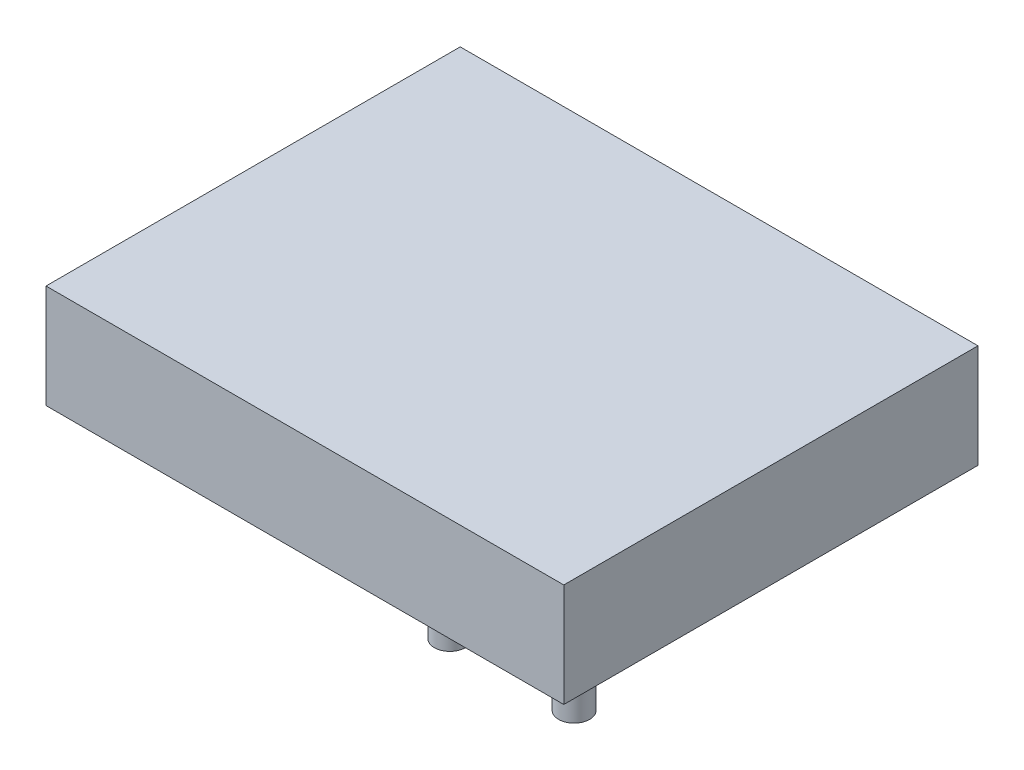
SolidWorks part; units mm, degrees
ref_plane "Płaszczyzna przednia" through (0, 0, 0) normal (0, 0, 1) x (1, 0, 0)
ref_plane "Płaszczyzna górna" through (0, 0, 0) normal (0, 1, 0) x (1, 0, 0)
ref_plane "Płaszczyzna prawa" through (0, 0, 0) normal (1, 0, 0) x (0, 0, -1)
sketch "Szkic1" plane through (0, 0, 0) normal (0, 0, 1) x (1, 0, 0)
  line L1 (-25, -5) -> (25, -5)
  line L2 (-25, -5) -> (-25, 5)
  line L3 (-25, 5) -> (25, 5)
  line L4 (25, -5) -> (25, 5)
  line L5 (-25, -5) -> (25, 5) construction
  line L6 (-25, 5) -> (25, -5) construction
  point P0 (0, 0)
  dimension "D1" = 50
  dimension "D2" = 10
extrude "Dodanie-wyciągnięcie1" add sketch "Szkic1" along normal blind 40
sketch "Szkic2" plane through (0, -5, 0) normal (0, -1, 0) x (1, 0, 0)
  line L0 (-25, 0) -> (25, 0) construction
  circle A0 centre (-6, 20) radius 1.5
  circle A1 centre (6, 20) radius 1.5
  dimension "D1" = 3
  dimension "D2" = 3
  dimension "D3" = 6
  dimension "D4" = 6
  dimension "D5" = 20
  dimension "D6" = 20
extrude "Dodanie-wyciągnięcie2" add sketch "Szkic2" along normal blind 20
